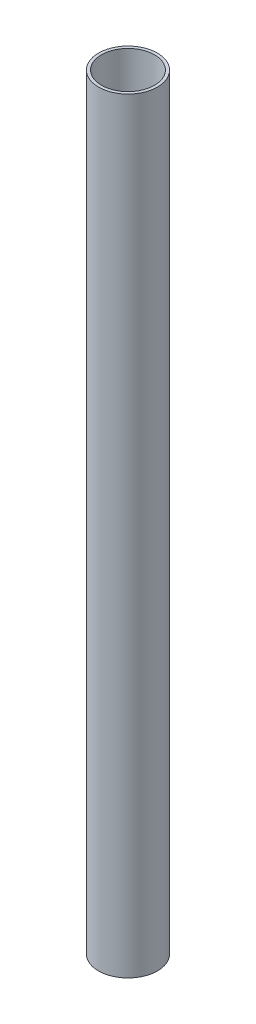
SolidWorks part; units mm, degrees
ref_plane "前视基准面" through (0, 0, 0) normal (0, 0, 1) x (1, 0, 0)
ref_plane "上视基准面" through (0, 0, 0) normal (0, 1, 0) x (1, 0, 0)
ref_plane "右视基准面" through (0, 0, 0) normal (1, 0, 0) x (0, 0, -1)
sketch "草图1" plane through (0, 0, 0) normal (0, 1, 0) x (1, 0, 0)
  circle A0 centre (0, 0) radius 10
  dimension "D1" = 20
extrude "1mm*30" add sketch "草图1" along normal mid plane 260 thin thin type one direction reverse wall 1
